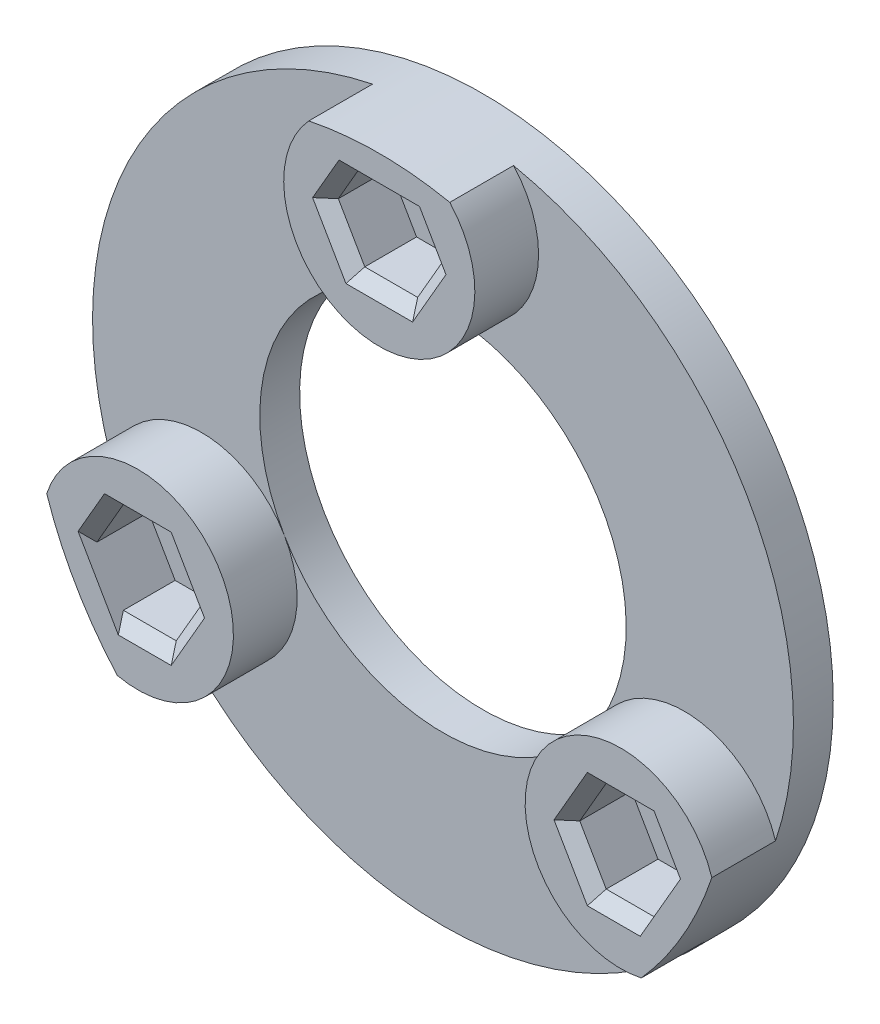
SolidWorks part; units mm, degrees
ref_plane "Front Plane" through (0, 0, 0) normal (0, 0, 1) x (1, 0, 0)
ref_plane "Top Plane" through (0, 0, 0) normal (0, 1, 0) x (1, 0, 0)
ref_plane "Right Plane" through (0, 0, 0) normal (1, 0, 0) x (0, 0, -1)
sketch "Sketch1" plane through (0, 0, 0) normal (0, 0, 1) x (1, 0, 0)
  circle A0 centre (0, 0) radius 22
  circle A1 centre (0, 0) radius 11.5
  circle A2 centre (0, 0) radius 17.5 construction
  circle A3 centre (0, 17.5) radius 1.65
  circle A4 centre (15.1554, -8.75) radius 1.65
  circle A6 centre (-15.1554, -8.75) radius 1.65
  point P13 (0, 0)
  dimension "D1" = 44
  dimension "D2" = 23
  dimension "D3" = 35
  dimension "D4" = 3.3
  dimension "D5" = 3
extrude "Boss-Extrude1" add sketch "Sketch1" along normal blind 2.5
sketch "Sketch2" plane through (0, 0, 2.5) normal (0, 0, 1) x (1, 0, 0)
  line L0 (55, 0) -> (-55, 0) construction
  line L1 (3.3198, 17.5) -> (1.6599, 20.375)
  line L2 (1.6599, 20.375) -> (-1.6599, 20.375)
  line L3 (-1.6599, 20.375) -> (-3.3198, 17.5)
  line L4 (-3.3198, 17.5) -> (-1.6599, 14.625)
  line L5 (-1.6599, 14.625) -> (1.6599, 14.625)
  line L6 (1.6599, 14.625) -> (3.3198, 17.5)
  line L7 (13.4956, -11.625) -> (16.8153, -11.625)
  line L8 (16.8153, -11.625) -> (18.4752, -8.75)
  line L9 (18.4752, -8.75) -> (16.8153, -5.875)
  line L10 (16.8153, -5.875) -> (13.4956, -5.875)
  line L11 (13.4956, -5.875) -> (11.8357, -8.75)
  line L12 (11.8357, -8.75) -> (13.4956, -11.625)
  line L13 (-16.8153, -5.875) -> (-18.4752, -8.75)
  line L14 (-18.4752, -8.75) -> (-16.8153, -11.625)
  line L15 (-16.8153, -11.625) -> (-13.4956, -11.625)
  line L16 (-13.4956, -11.625) -> (-11.8357, -8.75)
  line L17 (-11.8357, -8.75) -> (-13.4956, -5.875)
  line L18 (-13.4956, -5.875) -> (-16.8153, -5.875)
  arc A0 (-3.7475, 22.1857) -> (3.7475, 22.1857) centre (0, 17.5) ccw
  circle A1 centre (0, 17.5) radius 2.875 construction
  circle A2 centre (0, 0) radius 22.5 construction
  arc A3 (-3.7475, 22.1857) -> (3.7475, 22.1857) centre (0, 0) cw
  circle A4 centre (0, 17.5) radius 1.65
  arc A5 (21.0872, -7.8474) -> (17.3396, -14.3383) centre (0, 0) cw
  arc A6 (21.0872, -7.8474) -> (17.3396, -14.3383) centre (15.1554, -8.75) ccw
  arc A7 (-17.3396, -14.3383) -> (-21.0872, -7.8474) centre (0, 0) cw
  arc A8 (-17.3396, -14.3383) -> (-21.0872, -7.8474) centre (-15.1554, -8.75) ccw
  point P38 (0, 0)
  circle M11 centre (0, 0) radius 22
  dimension "D1" = 5.75
  dimension "D2" = 6
  dimension "D3" = 22.5
  dimension "D4" = 3.3
  dimension "D5" = 3
extrude "Boss-Extrude2" add sketch "Sketch2" along normal blind 4 contours A0 L6 L5 L4 L3 L2 L1 M11 | A8 L18 L17 L16 L15 L14 L13 M11 | A6 L12 L11 L10 L9 L8 L7 M11
chamfer "Chamfer1" distance 0.75 angle 45 15 edges at (15.1554, -11.625, 6.5) (17.6453, -7.3125, 6.5) (15.1554, -5.875, 6.5) (12.6656, -7.3125, 6.5) (12.6656, -10.1875, 6.5) (-15.1554, -11.625, 6.5) (-12.6656, -10.1875, 6.5) (-12.6656, -7.3125, 6.5) (-15.1554, -5.875, 6.5) (-17.6453, -7.3125, 6.5) (-2.4898, 18.9375, 6.5) (-2.4898, 16.0625, 6.5) (0, 14.625, 6.5) (2.4898, 16.0625, 6.5) (2.4898, 18.9375, 6.5)
